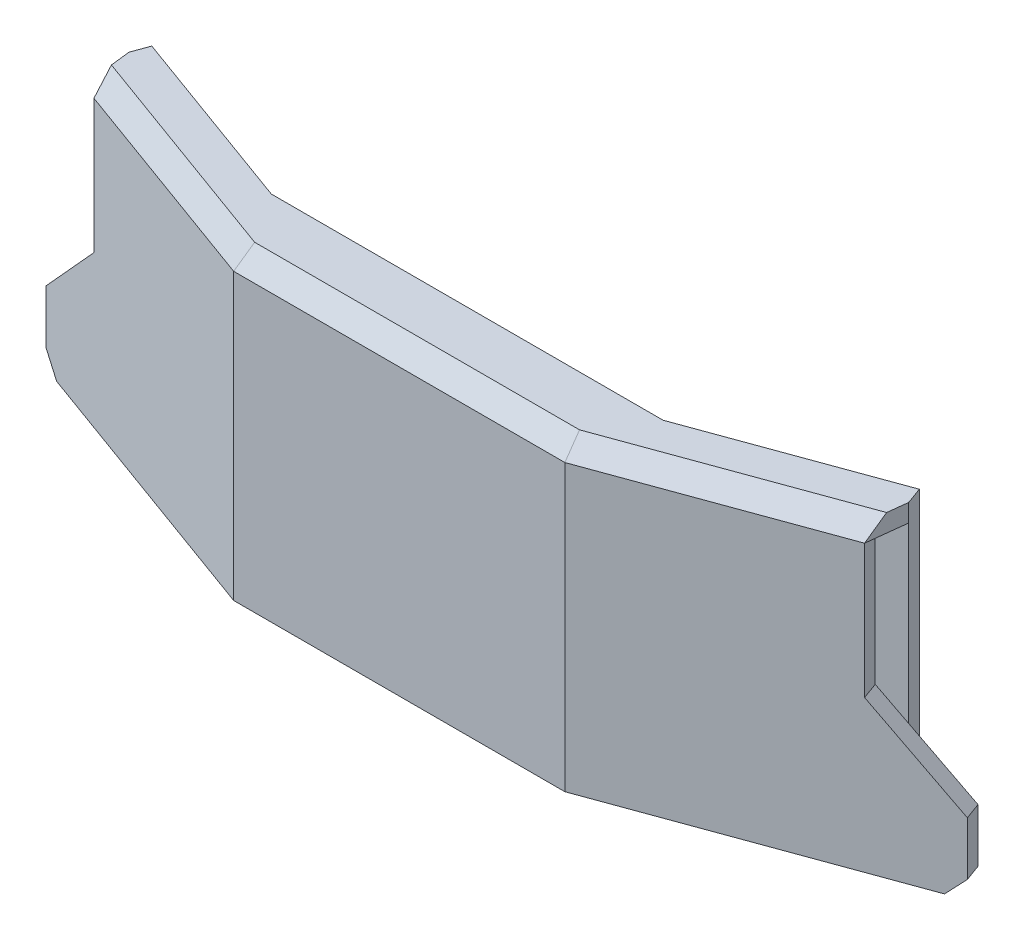
SolidWorks part; units mm, degrees
ref_plane "Front Plane" through (0, 0, 0) normal (0, 0, 1) x (1, 0, 0)
ref_plane "Top Plane" through (0, 0, 0) normal (0, 1, 0) x (1, 0, 0)
ref_plane "Right Plane" through (0, 0, 0) normal (1, 0, 0) x (0, 0, -1)
sketch "Sketch5" plane through (0, 0, 0) normal (0, 1, 0) x (1, 0, 0)
  line L0 (-40, 10.0509) -> (-40.684, 8.1715)
  line L1 (-40.684, 8.1715) -> (-42.5634, 8.8555)
  line L2 (-42.5634, 8.8555) -> (-43.2475, 6.9761)
  line L3 (-43.2475, 6.9761) -> (-18.5857, -2)
  line L4 (40, 10.0509) -> (40.684, 8.1715)
  line L5 (40.684, 8.1715) -> (42.5634, 8.8555)
  line L6 (42.5634, 8.8555) -> (43.2475, 6.9761)
  line L7 (43.2475, 6.9761) -> (18.5857, -2)
  line L8 (-18.5857, -2) -> (18.5857, -2)
  line L9 (-40, 10.0509) -> (-43.7588, 11.419)
  line L10 (-43.7588, 11.419) -> (-43.0747, 13.2983)
  line L11 (-43.0747, 13.2983) -> (-37.4366, 11.2462)
  line L12 (-37.4366, 11.2462) -> (-37.4366, 6.9895)
  line L13 (-37.4366, 6.9895) -> (-18.2331, 0)
  line L14 (-18.2331, 0) -> (18.2331, 0)
  line L15 (18.2331, 0) -> (37.4366, 6.9895)
  line L16 (40, 10.0509) -> (43.7588, 11.419)
  line L17 (43.7588, 11.419) -> (43.0747, 13.2983)
  line L18 (43.0747, 13.2983) -> (37.4366, 11.2462)
  line L19 (37.4366, 11.2462) -> (37.4366, 6.9895)
  point P20 (0, 0)
  dimension "D1" = 2
  dimension "D2" = 2
  dimension "D3" = 2
  dimension "D4" = 6
  dimension "D5" = 4
  dimension "D6" = 2
  dimension "D7" = 2
  dimension "D8" = 2
  dimension "D9" = 2
  dimension "D10" = 20.436
  dimension "D11" = 26.2445
  dimension "D12" = 110
  dimension "D14" = 37.1714
  dimension "D20" = 4.2567
  dimension "D21" = 110
extrude "Boss-Extrude5" add sketch "Sketch5" along normal blind 30
sketch "Sketch6" plane through (0, 30, 0) normal (0, 1, 0) x (1, 0, 0)
  line L0 (-43.7588, 11.419) -> (-43.2475, 6.9761)
  line L1 (-43.2475, 6.9761) -> (-18.5857, -2)
  line L2 (-18.5857, -2) -> (18.5857, -2)
  line L3 (18.5857, -2) -> (43.2475, 6.9761)
  line L4 (43.2475, 6.9761) -> (43.7588, 11.419)
  line L5 (43.7588, 11.419) -> (43.0747, 13.2983)
  line L13 (-43.0747, 13.2983) -> (-43.7588, 11.419)
  line L15 (-43.0747, 13.2983) -> (-37.4366, 11.2462)
  line L17 (43.0747, 13.2983) -> (37.4366, 11.2462)
  line L18 (37.4366, 11.2462) -> (21.9872, 5.6231)
  line L19 (-37.4366, 11.2462) -> (-21.9872, 5.6231)
  line L20 (21.9872, 5.6231) -> (-21.9872, 5.6231)
  dimension "D1" = 7.6231
extrude "Boss-Extrude6" add sketch "Sketch6" along normal blind 2
sketch "Sketch7" plane through (0, 0, 0) normal (0, -1, 0) x (1, 0, 0)
  line L0 (-43.2475, -6.9761) -> (-42.5634, -8.8555)
  line L1 (-42.5634, -8.8555) -> (-18.2331, 0)
  line L2 (-18.2331, 0) -> (18.2331, 0)
  line L3 (18.2331, 0) -> (42.5634, -8.8555)
  line L4 (42.5634, -8.8555) -> (43.2475, -6.9761)
  line L5 (43.2475, -6.9761) -> (18.5857, 2)
  line L6 (18.5857, 2) -> (-18.5857, 2)
  line L7 (-18.5857, 2) -> (-43.2475, -6.9761)
extrude "Boss-Extrude7" add sketch "Sketch7" along normal blind 2
chamfer "Chamfer2" distance 2 angle 45 3 edges at (30.9166, 32, -2.4881) (0, 32, 2) (-30.9166, 32, -2.4881)
chamfer "Chamfer3" distance 2 angle 45 2 edges at (-42.9054, -2, -7.9158) (42.9054, -2, -7.9158)
sketch "Sketch10" plane through (-2.8169, 0, 7.7394) normal (-0.342, 0, 0.9397) x (0.9397, 0, 0.342)
  line L0 (-41.0253, -2) -> (-43.0253, 0)
  line L1 (-45.0253, 0) -> (-41.0253, 0) construction
  line L2 (-43.0253, 0) -> (-43.0253, 15)
  line L3 (-43.0253, 30) -> (-43.0253, 0) construction
  line L4 (-43.0253, 15) -> (-52.0253, 6)
  line L5 (-52.0253, -2) -> (-41.0253, -2)
  line L6 (-52.0253, 6) -> (-52.0253, -2)
  dimension "D1" = 45
  dimension "D2" = 8
extrude "Boss-Extrude8" add sketch "Sketch10" against normal up to surface (2 mm away) up to face at (-35.3909, 12.8889, -6.2449)
sketch "Sketch11" plane through (2.8169, 0, 7.7394) normal (0.342, 0, 0.9397) x (0.9397, 0, -0.342)
  line L0 (41.0253, -2) -> (43.0253, 0)
  line L1 (41.0253, 0) -> (45.0253, 0) construction
  line L2 (43.0253, 0) -> (43.0253, 15)
  line L3 (43.0253, 30) -> (43.0253, 0) construction
  line L4 (43.0253, 15) -> (52.0253, 6)
  line L5 (52.0253, -2) -> (41.0253, -2)
  line L6 (52.0253, 6) -> (52.0253, -2)
  dimension "D1" = 45
  dimension "D2" = 8
extrude "Boss-Extrude9" add sketch "Sketch11" against normal up to surface (2 mm away) up to face at (35.3909, 12.8889, -6.2449)
chamfer "Chamfer4" distance 2 angle 45 2 edges at (-51.3627, -2, -10.994) (51.3627, -2, -10.994)
